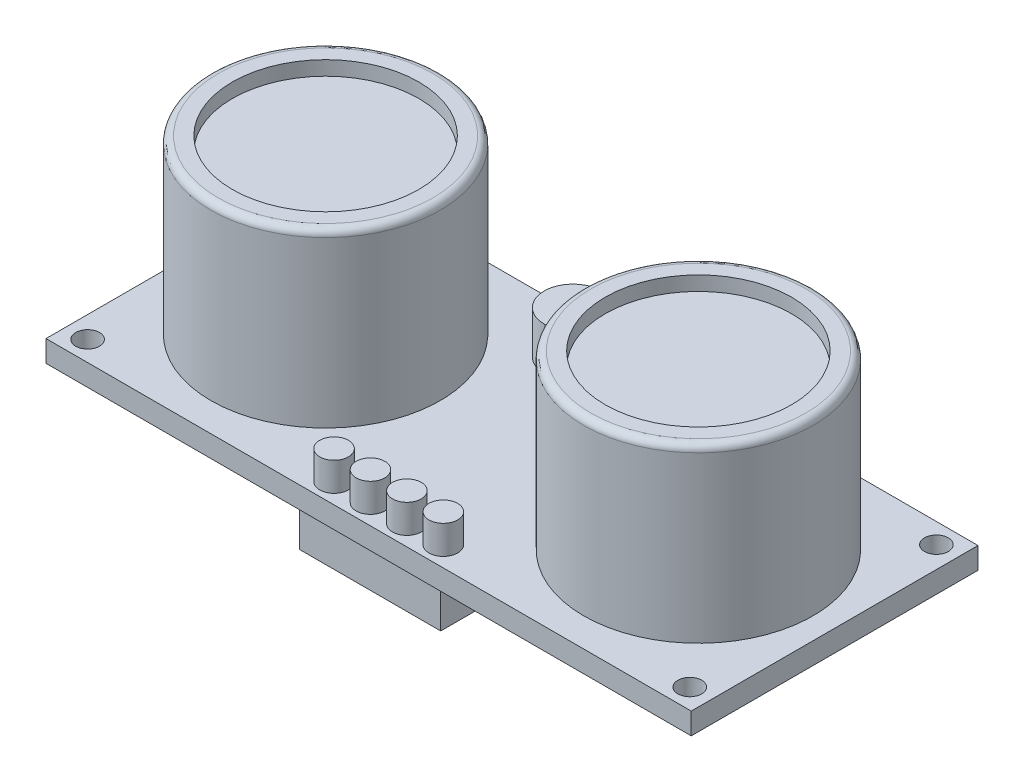
SolidWorks part; units mm, degrees
ref_plane "Front Plane" through (0, 0, 0) normal (0, 0, 1) x (1, 0, 0)
ref_plane "Top Plane" through (0, 0, 0) normal (0, 1, 0) x (1, 0, 0)
ref_plane "Right Plane" through (0, 0, 0) normal (1, 0, 0) x (0, 0, -1)
sketch "Sketch1" plane through (0, 0, 0) normal (0, 1, 0) x (1, 0, 0)
  line L1 (-22.5, -10) -> (22.5, -10)
  line L2 (-22.5, -10) -> (-22.5, 10)
  line L3 (-22.5, 10) -> (22.5, 10)
  line L4 (22.5, -10) -> (22.5, 10)
  point P4 (0, -10)
  point P6 (22.5, 0)
  dimension "D1" = 45
  dimension "D2" = 20
extrude "Boss-Extrude1" add sketch "Sketch1" along normal blind 1.5
sketch "Sketch2" plane through (0, 1.5, 0) normal (0, 1, 0) x (1, 0, 0)
  line L0 (22.5, 10) -> (-22.5, 10) construction
  line L1 (-3, 5.25) -> (3, 5.25)
  line L3 (-3, 9.25) -> (3, 9.25)
  arc A0 (-3, 9.25) -> (-3, 5.25) centre (-3, 7.25) ccw
  arc A1 (3, 5.25) -> (3, 9.25) centre (3, 7.25) ccw
  point P5 (5, 7.25)
  point P7 (0, 0)
  point P8 (6.949, 6.6675)
  point P11 (-5, 7.25)
  point P12 (0, 10)
  point P13 (0, 9.25)
  point P14 (3, 9.2936)
  point P15 (3, 7.2936)
  point P16 (-3, 7.2936)
  point P17 (-5, 5.554)
  point P18 (3, 5)
  point P19 (3, 7)
  point P20 (0, 0)
  point P21 (0, 0)
  point P22 (0, 0)
  point P23 (-3, 7)
  point P24 (-5, 6.2529)
  point P25 (0, 0)
  point P26 (3, 8.2529)
  point P27 (-3, 4.2529)
  point P28 (-3, 6.2529)
  point P29 (0, 0)
  dimension "D1" = 10
  dimension "D4" = 2
  dimension "D2" = 4
  dimension "D3" = 0.75
extrude "Boss-Extrude2" add sketch "Sketch2" along normal blind 3
sketch "Sketch3" plane through (0, 1.5, 0) normal (0, 1, 0) x (1, 0, 0)
  line L0 (-21, -8.6) -> (-21, 8.6) construction
  line L1 (-21, -8.6) -> (21, -8.6) construction
  circle A0 centre (-21, 8.6) radius 0.83
  circle A1 centre (-21, -8.6) radius 0.83
  circle A2 centre (21, -8.6) radius 0.83
  circle A3 centre (21, 8.6) radius 0.83
  point P8 (0, 0)
  point P9 (0, 0)
  point P10 (0, 0)
  point P14 (-21, 0)
  point P17 (0, -8.6)
  dimension "D3" = 1.66
  dimension "D1" = 17.2
  dimension "D2" = 42
sketch "Sketch4" plane through (0, 1.5, 0) normal (0, 1, 0) x (1, 0, 0)
  line L0 (-13, 0) -> (13, 0) construction
  circle A0 centre (-13, 0) radius 8
  circle A1 centre (13, 0) radius 8
  point P4 (-14.0223, 0)
  point P5 (-13.1844, -1.257)
  point P6 (-12.5698, -0.3631)
  point P7 (0, 0)
  point P9 (0, 0)
  dimension "D1" = 16
  dimension "D2" = 26
extrude "Boss-Extrude3" add sketch "Sketch4" along normal blind 12
sketch "Sketch5" plane through (0, 13.5, 0) normal (0, 1, 0) x (1, 0, 0)
  circle A0 centre (-13, 0) radius 6.5
  circle A1 centre (13, 0) radius 6.5
  circle A2 centre (13, 0) radius 8 construction
  circle A3 centre (-13, 0) radius 8 construction
  circle A4 centre (13, 0) radius 8 construction
  dimension "D1" = 1.5
extrude "Cut-Extrude1" cut sketch "Sketch5" against normal blind 1
sketch "Sketch6" plane through (0, 1.5, 0) normal (0, 1, 0) x (1, 0, 0)
  line L0 (-21, -8.6) -> (21, -8.6) construction
  line L1 (-3.81, -8.6) -> (-1.27, -8.6) construction
  line L2 (-1.27, -8.6) -> (1.27, -8.6) construction
  circle A0 centre (-3.81, -8.6) radius 1
  circle A3 centre (-1.27, -8.6) radius 1
  circle A4 centre (1.27, -8.6) radius 1
  circle A5 centre (3.81, -8.6) radius 1
  point P4 (0, 0)
  point P14 (0, -8.6)
  point P15 (0, 0)
  point P16 (0, 0)
  dimension "D3" = 2
  dimension "D2" = 2.54
  dimension "D1" = 4
extrude "Boss-Extrude4" add sketch "Sketch6" along normal blind 2
fillet "Fillet1" radius 0.5 2 edges at (13, 13.5, 8) (-13, 13.5, 8)
extrude "Cut-Extrude2" cut sketch "Sketch3" against normal up to next
sketch "Sketch7" plane through (0, 0, 0) normal (0, -1, 0) x (1, 0, 0)
  line L0 (-22.5, 10) -> (22.5, 10) construction
  line L1 (-4.9293, 7.2605) -> (4.9293, 7.2605)
  line L2 (-4.9293, 7.2605) -> (-4.9293, 9.9)
  line L3 (-4.9293, 9.9) -> (4.9293, 9.9)
  line L4 (4.9293, 7.2605) -> (4.9293, 9.9)
  point P6 (0, 10)
  point P7 (0, 7.2605)
  dimension "D1" = 0.1
  dimension "D2" = 9.8585
  dimension "D3" = 2.6395
extrude "Boss-Extrude5" add sketch "Sketch7" along normal blind 2.5
